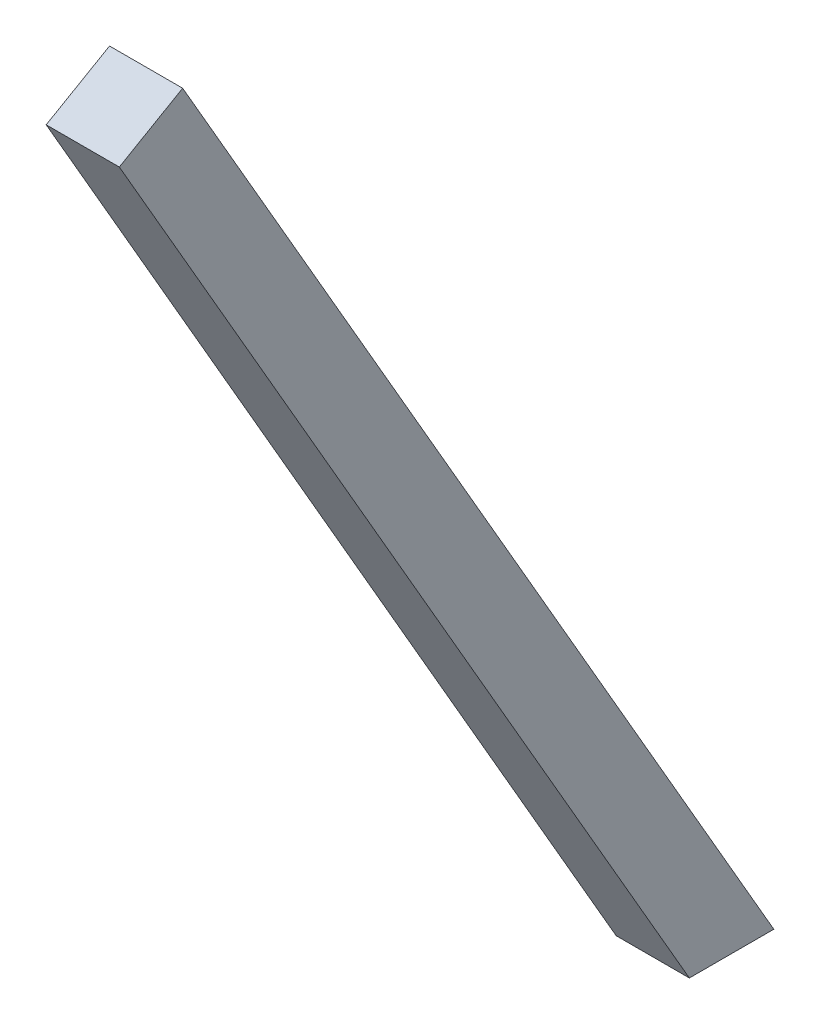
SolidWorks part; units mm, degrees
ref_plane "Front Plane" through (0, 0, 0) normal (0, 0, 1) x (1, 0, 0)
ref_plane "Top Plane" through (0, 0, 0) normal (0, 1, 0) x (1, 0, 0)
ref_plane "Right Plane" through (0, 0, 0) normal (1, 0, 0) x (0, 0, -1)
sketch "Sketch2" plane through (0, 0, 0) normal (1, 0, 0) x (0, 0, -1)
  line L0 (0, 0) -> (-197.9734, 342.9)
  line L1 (-197.9734, 342.9) -> (-175.9764, 355.6)
  line L2 (-175.9764, 355.6) -> (29.3294, 0)
  line L3 (29.3294, 0) -> (0, 0)
  line L4 (0, 0) -> (21.997, 12.7) construction
  line L5 (0, 0) -> (-8.7538, 0) construction
  line L6 (-175.9764, 355.6) -> (-180.2307, 348.2312) construction
  line L7 (-175.9764, 355.6) -> (-175.9764, 0) construction
  line L8 (-175.9764, 0) -> (29.3294, 0) construction
  dimension "D1" = 25.4
  dimension "D2" = 355.6
  dimension "D3" = 60
  dimension "D4" = 60
extrude "Boss-Extrude1" add sketch "Sketch2" along normal blind 25.4
